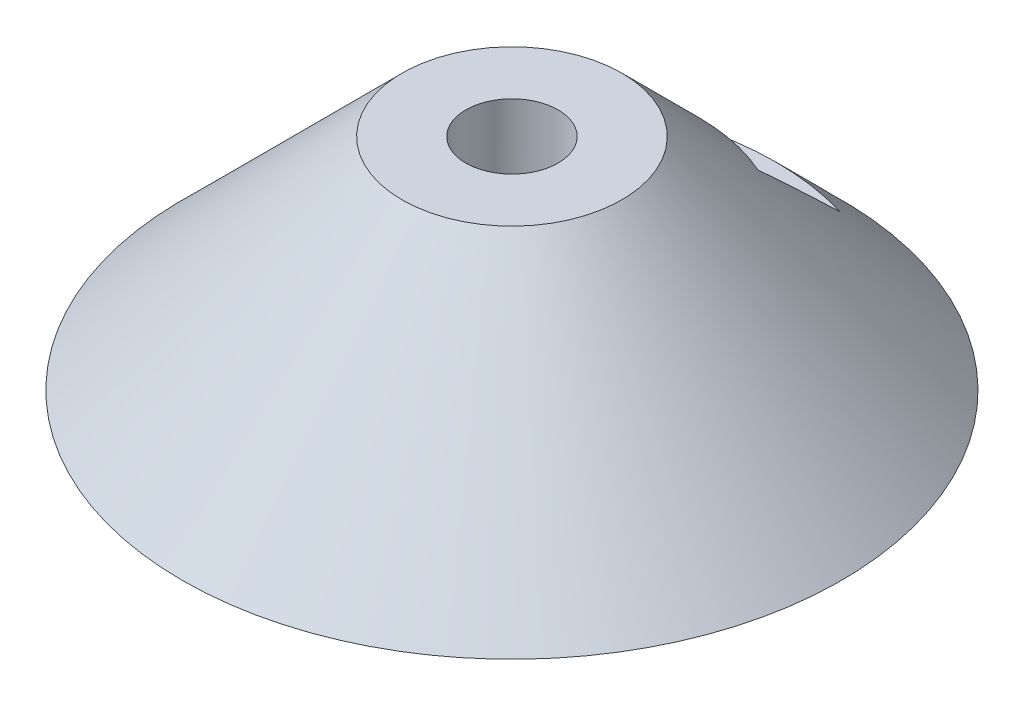
SolidWorks part; units mm, degrees
ref_plane "Front Plane" through (0, 0, 0) normal (0, 0, 1) x (1, 0, 0)
ref_plane "Top Plane" through (0, 0, 0) normal (0, 1, 0) x (1, 0, 0)
ref_plane "Right Plane" through (0, 0, 0) normal (1, 0, 0) x (0, 0, -1)
sketch "Sketch2" plane through (0, 0, 0) normal (0, 0, 1) x (1, 0, 0)
  line L0 (0, 0) -> (0, 20) construction
  line L1 (0, 20) -> (10, 20)
  line L2 (10, 20) -> (30, 0)
  line L3 (30, 0) -> (0, 0)
  line L4 (0, 0) -> (0, 20)
  dimension "D1" = 20
  dimension "D2" = 30
  dimension "D3" = 10
revolve "Revolve1" add sketch "Sketch2" angle 360 about L0
sketch "Sketch3" plane through (0, 20, 0) normal (0, 1, 0) x (1, 0, 0)
  circle A0 centre (0, 0) radius 4.2
  dimension "D1" = 8.4
extrude "Cut-Extrude1" cut sketch "Sketch3" against normal blind 10
sketch3d "3DSketch2" plane through (0, 0, 0) normal (0, 0, 1) x (1, 0, 0)
sketch "Sketch6" plane through (0, 0, 0) normal (0, 0, 1) x (1, 0, 0)
  line L0 (6.85, 13) -> (-6.85, 13)
  line L1 (6.85, 13) -> (6.85, 6)
  line L2 (-6.85, 13) -> (-6.85, 6)
  line L3 (6.85, 6) -> (-6.85, 6)
  line L4 (6.85, 13) -> (-6.85, 6) construction
  line L5 (-6.85, 13) -> (6.85, 6) construction
  line L6 (-30, 0) -> (30, 0) construction
  point P0 (0, 10.3243)
  point P1 (0, 9.5)
  dimension "D1" = 7
  dimension "D2" = 13.7
  dimension "D3" = 6
extrude "Cut-Extrude8" cut sketch "Sketch6" against normal blind 59
sketch "Sketch7" plane through (0, 6, 0) normal (0, 1, 0) x (1, 0, 0)
  line L0 (-6.85, 0) -> (6.85, 0) construction
  line L1 (6.85, -3.9548) -> (6.85, 3.9548)
  line L2 (6.85, 3.9548) -> (0, 7.9097)
  line L3 (0, 7.9097) -> (-6.85, 3.9548)
  line L4 (-6.85, 3.9548) -> (-6.85, -3.9548)
  line L5 (-6.85, -3.9548) -> (0, -7.9097)
  line L6 (0, -7.9097) -> (6.85, -3.9548)
  line L7 (-6.85, 23.0017) -> (-6.85, 0) construction
  circle A0 centre (0, 0) radius 6.85 construction
  dimension "D1" = 13.7
extrude "Cut-Extrude9" cut sketch "Sketch7" along normal blind 7
sketch "Sketch8" plane through (0, 0, 0) normal (0, 0, 1) x (1, 0, 0)
  line L0 (-1, -2) -> (1, -2)
  line L1 (-1, -2) -> (-1, 2)
  line L2 (1, -2) -> (1, 2)
  line L3 (-1, 2) -> (1, 2)
  line L4 (-1, -2) -> (1, 2) construction
  line L5 (1, -2) -> (-1, 2) construction
  line L6 (-30, 0) -> (30, 0) construction
  point P1 (0, 0)
  dimension "D1" = 4
  dimension "D2" = 2
extrude "Cut-Extrude10" cut sketch "Sketch8" against normal blind 61
